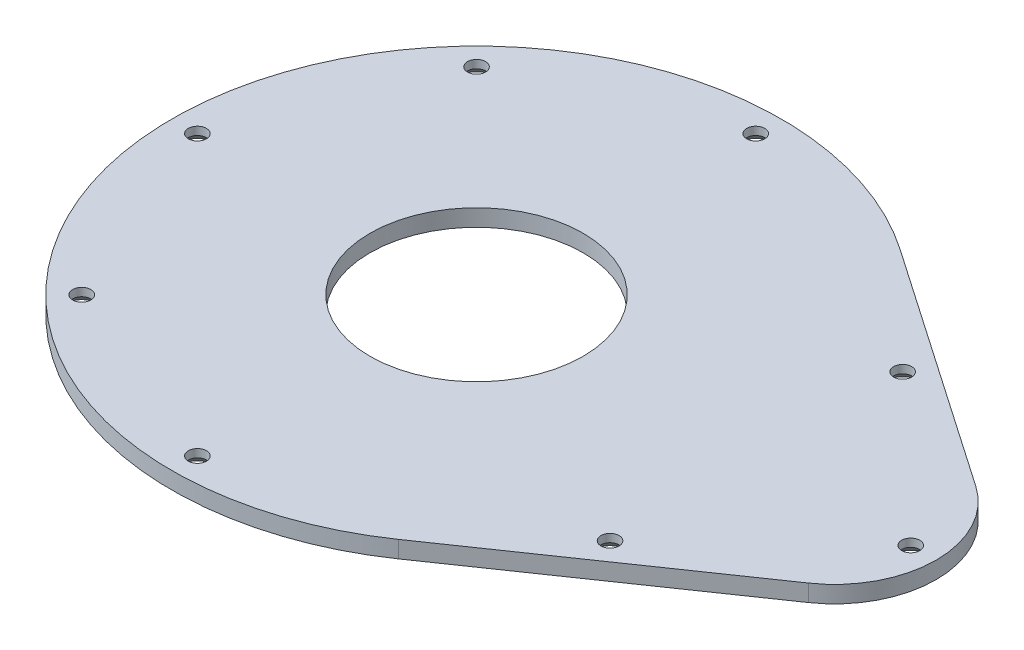
SolidWorks part; units mm, degrees
material "6061 Alloy"
ref_plane "Front Plane" through (0, 0, 0) normal (0, 0, 1) x (1, 0, 0)
ref_plane "Top Plane" through (0, 0, 0) normal (0, 1, 0) x (1, 0, 0)
ref_plane "Right Plane" through (0, 0, 0) normal (1, 0, 0) x (0, 0, -1)
sketch "Sketch1" plane through (0, 0, 0) normal (0, 1, 0) x (1, 0, 0)
  circle A0 centre (0, 0) radius 57.15
  circle A1 centre (0, 0) radius 20
  dimension "D1" = 40
  dimension "D2" = 114.3
extrude "Boss-Extrude1" add sketch "Sketch1" against normal blind 3.175
sketch "Sketch2" plane through (0, -3.175, 0) normal (0, -1, 0) x (-1, 0, 0)
  line L0 (-32.4102, 47.0712) -> (-77.9864, 15.6904)
  line L1 (-32.4102, -47.0712) -> (-77.9864, -15.6904)
  arc A0 (-77.9864, 15.6904) -> (-77.9864, -15.6904) centre (-67.183, 0) ccw
  circle A1 centre (0, 0) radius 57.15 construction
  circle A2 centre (0, 0) radius 57.15 construction
  arc A4 (-32.4102, 47.0712) -> (-32.4102, -47.0712) centre (0, 0) ccw
  dimension "D2" = 19.05
  dimension "D1" = 67.183
extrude "Boss-Extrude2" add sketch "Sketch2" against normal up to surface (3.175 mm away) up to face at (0, 0, 20)
hole_wizard "CSK for M3 SFHCS1" positions "Sketch6" profile "Sketch7" countersink size "M3" standard "Ansi Metric" end condition through all
sketch "Sketch6" plane through (0, -3.175, 0) normal (0, -1, 0) x (1, 0, 0)
  line L0 (77.9864, 15.6904) -> (32.4102, 47.0712) construction
  line L1 (32.4102, -47.0712) -> (77.9864, -15.6904) construction
  line L2 (77.9864, 15.6904) -> (32.4102, 47.0712) construction
  line L3 (32.4102, -47.0712) -> (77.9864, -15.6904) construction
  line L4 (29.7022, -43.1382) -> (75.2783, -11.7573) construction
  line L5 (75.2783, 11.7573) -> (29.7022, 43.1382) construction
  line L6 (0, 0) -> (-37.0346, 37.0346) construction
  line L8 (0, 0) -> (0, 50000) construction
  arc A0 (32.4102, 47.0712) -> (32.4102, -47.0712) centre (0, 0) ccw construction
  arc A1 (77.9864, -15.6904) -> (77.9864, 15.6904) centre (67.183, 0) ccw construction
  arc A2 (32.4102, 47.0712) -> (32.4102, -47.0712) centre (0, 0) ccw construction
  arc A3 (77.9864, -15.6904) -> (77.9864, 15.6904) centre (67.183, 0) ccw construction
  arc A4 (29.7022, 43.1382) -> (29.7022, -43.1382) centre (0, 0) ccw construction
  arc A5 (75.2783, -11.7573) -> (75.2783, 11.7573) centre (67.183, 0) ccw construction
  point P18 (0, 52.3748)
  point P20 (-52.3748, 0)
  point P22 (-37.0346, -37.0346)
  point P24 (0, -52.3748)
  point P26 (52.4903, -27.4478)
  point P28 (81.4578, 0)
  point P30 (52.4903, 27.4478)
  point P35 (-37.0346, 37.0346)
  dimension "D2" = 45
  dimension "D1" = 4.7752
sketch "Sketch7" plane through (0, -3.175, 52.3748) normal (1, 0, 0) x (0, 0, -1)
  line L0 (0, 0) -> (0, 3.175)
  line L1 (0, 3.175) -> (1.7, 3.175)
  line L2 (1.7, 3.175) -> (1.7, 1.66)
  line L3 (1.7, 1.66) -> (3.36, 0)
  line L5 (3.36, 0) -> (0, 0)
  line L6 (-1.7, 1.66) -> (-3.36, 0) construction
  line L11 (0, -6.35) -> (0, 107.95) construction
  dimension "Thru Hole Dia." = 3.4
  dimension "Thru Hole Depth" = 3.175
  dimension "Near C'Sink Dia." = 6.72
  dimension "Near C'Sink Angle" = 90
